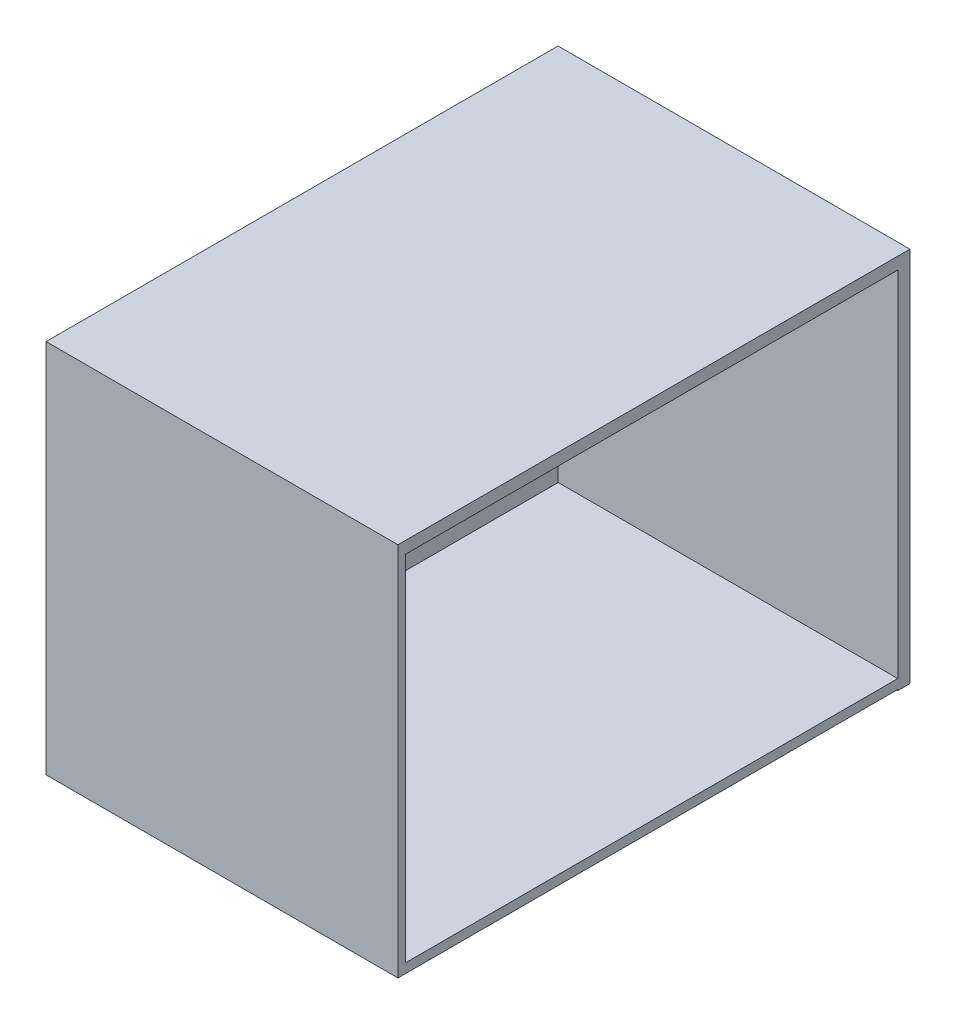
SolidWorks part; units mm, degrees
ref_plane "Front Plane" through (0, 0, 0) normal (0, 0, 1) x (1, 0, 0)
ref_plane "Top Plane" through (0, 0, 0) normal (0, 1, 0) x (1, 0, 0)
ref_plane "Right Plane" through (0, 0, 0) normal (1, 0, 0) x (0, 0, -1)
sketch "Sketch1" plane through (0, 0, 0) normal (1, 0, 0) x (0, 0, -1)
  line L1 (-109.1133, 51.4956) -> (-26.1853, 51.4956)
  line L2 (-109.1133, 51.4956) -> (-109.1133, -9.2809)
  line L3 (-109.1133, -9.2809) -> (-26.1853, -9.2809)
  line L4 (-26.1853, 51.4956) -> (-26.1853, -9.2809)
extrude "Boss-Extrude1" add sketch "Sketch1" along normal blind 2
sketch "Sketch2" plane through (2, 0, 0) normal (1, 0, 0) x (0, 0, -1)
  line L0 (-26.1853, -9.2809) -> (-26.1853, 51.4956) construction
  line L1 (-109.1133, 51.4956) -> (-26.1853, 51.4956)
  line L2 (-109.1133, 51.4956) -> (-109.1133, 49.5511)
  line L3 (-109.1133, 49.5511) -> (-26.1853, 49.5511)
  line L4 (-26.1853, 51.4956) -> (-26.1853, 49.5511)
extrude "Boss-Extrude2" add sketch "Sketch2" along normal blind 55
sketch "Sketch3" plane through (2, 0, 0) normal (1, 0, 0) x (0, 0, -1)
  line L0 (-26.1853, -9.2809) -> (-26.1853, 49.5511) construction
  line L1 (-109.1133, -9.2809) -> (-26.1853, -9.2809)
  line L2 (-109.1133, -9.2809) -> (-109.1133, -7.758)
  line L3 (-109.1133, -7.758) -> (-26.1853, -7.758)
  line L4 (-26.1853, -9.2809) -> (-26.1853, -7.758)
extrude "Boss-Extrude3" add sketch "Sketch3" along normal blind 55
sketch "Sketch4" plane through (2, 0, 0) normal (1, 0, 0) x (0, 0, -1)
  line L0 (-26.1853, -7.758) -> (-109.1133, -7.758) construction
  line L1 (-109.1133, 49.5511) -> (-107.875, 49.5511)
  line L2 (-109.1133, 49.5511) -> (-109.1133, -7.758)
  line L3 (-109.1133, -7.758) -> (-107.875, -7.758)
  line L4 (-107.875, 49.5511) -> (-107.875, -7.758)
extrude "Boss-Extrude4" add sketch "Sketch4" along normal blind 55
sketch "Sketch5" plane through (0, 49.5511, 0) normal (0, -1, 0) x (-1, 0, 0)
  line L1 (-2, -107.875) -> (-2, -26.1853) construction
  line L2 (-57, -26.1853) -> (-2, -26.1853)
  line L3 (-57, -26.1853) -> (-57, -28.1536)
  line L4 (-57, -28.1536) -> (-2, -28.1536)
  line L5 (-2, -26.1853) -> (-2, -28.1536)
extrude "Boss-Extrude5" add sketch "Sketch5" along normal blind 59
sketch "Sketch6" plane through (0, 0, 0) normal (-1, 0, 0) x (0, 0, 1)
  line L1 (98.159, -0.5593) -> (56.6586, -0.5593)
  line L2 (98.159, -0.5593) -> (98.159, 30.0428)
  line L3 (98.159, 30.0428) -> (56.6586, 30.0428)
  line L4 (56.6586, -0.5593) -> (56.6586, 30.0428)
extrude "Cut-Extrude1" cut sketch "Sketch6" against normal blind 59
